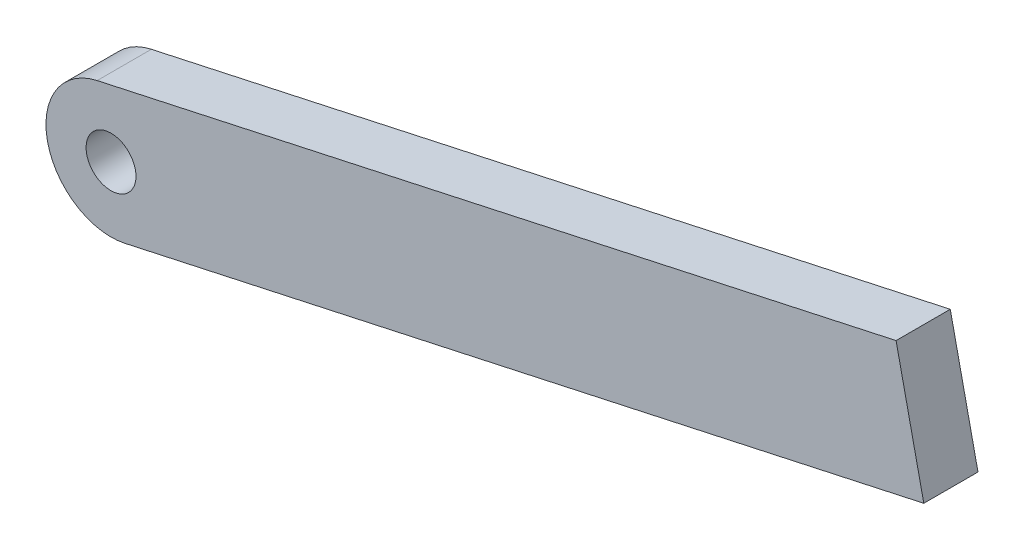
SolidWorks part; units mm, degrees
ref_plane "Front Plane" through (0, 0, 0) normal (0, 0, 1) x (1, 0, 0)
ref_plane "Top Plane" through (0, 0, 0) normal (0, 1, 0) x (1, 0, 0)
ref_plane "Right Plane" through (0, 0, 0) normal (1, 0, 0) x (0, 0, -1)
sketch "Sketch2" plane through (0, 0, 0) normal (0, 0, 1) x (1, 0, 0)
  line L0 (192.8629, 18.0099) -> (194.4871, 10.5651)
  line L1 (192.8629, 18.0099) -> (239.6629, 28.2199)
  line L2 (194.4871, 10.5651) -> (241.287, 20.775)
  line L3 (239.6629, 28.2199) -> (241.287, 20.775)
  circle A0 centre (193.675, 14.2875) radius 1.4605
  circle A1 centre (193.675, 14.2875) radius 3.81
  dimension "D1" = 7.62
  dimension "D2" = 2.921
  dimension "D3" = 47.9007
  dimension "D4" = 7.4449
extrude "Boss-Extrude1" add sketch "Sketch2" along normal blind 3.175 contours L1 L3 L2 L0 | A1
sketch "Sketch3" plane through (0, 0, 3.175) normal (0, 0, 1) x (1, 0, 0)
  circle A0 centre (193.675, 14.2875) radius 1.4605
  dimension "D1" = 2.921
extrude "Cut-Extrude1" cut sketch "Sketch3" against normal blind 3.175
